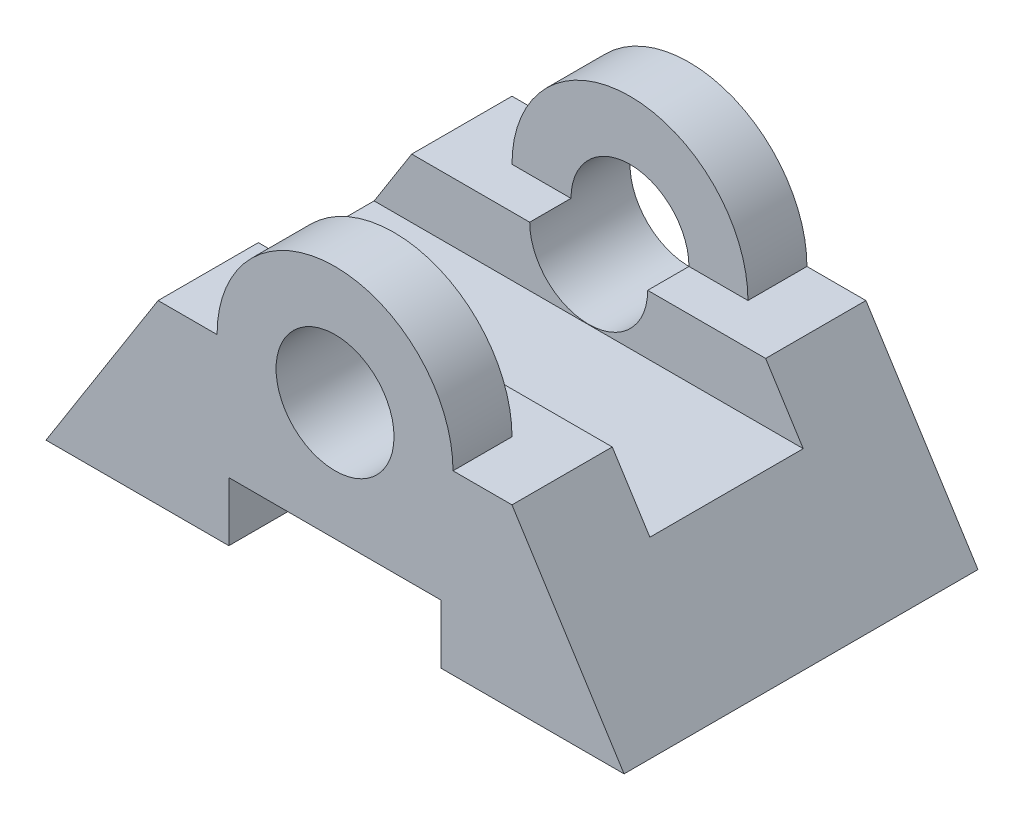
SolidWorks part; units mm, degrees
ref_plane "Front Plane" through (0, 0, 0) normal (0, 0, 1) x (1, 0, 0)
ref_plane "Top Plane" through (0, 0, 0) normal (0, 1, 0) x (1, 0, 0)
ref_plane "Right Plane" through (0, 0, 0) normal (1, 0, 0) x (0, 0, -1)
sketch "Sketch1" plane through (0, 0, 0) normal (0, 0, 1) x (1, 0, 0)
  line L0 (-49, 0) -> (-30, 30)
  line L1 (-30, 30) -> (-20, 30)
  line L2 (-49, 0) -> (-18, 0)
  line L3 (-18, 0) -> (-18, 10)
  line L4 (-18, 10) -> (18, 10)
  line L5 (18, 10) -> (18, 0)
  line L6 (0, 43.941) -> (0, -26.5577) construction
  line L7 (18, 0) -> (18, 10)
  line L8 (49, 0) -> (18, 0)
  line L9 (49, 0) -> (30, 30)
  line L10 (30, 30) -> (20, 30)
  line L11 (-20, 30) -> (20, 30)
  point P2 (0, 10)
  dimension "D1" = 36
  dimension "D2" = 98
  dimension "D3" = 10
  dimension "D4" = 10
  dimension "D5" = 30
extrude "Boss-Extrude1" add sketch "Sketch1" against normal blind 60 contours L6 L11 L1 L0 L2 L3 L4 | L11 L6 L4 L5 L8 L9 L10
ref_plane "Plane1" through (30, 0, 0) normal (1, 0, 0) x (0, 0, -1)
sketch "Sketch3" plane through (30, 0, 0) normal (1, 0, 0) x (0, 0, -1)
  line L0 (17, 30) -> (17, 19.937)
  line L1 (60, 30) -> (0, 30) construction
  line L2 (17, 19.937) -> (43, 19.937)
  line L3 (43, 19.937) -> (43, 30)
  point P4 (0, 0)
  dimension "D1" = 17
  dimension "D2" = 26
extrude "Cut-Extrude1" cut sketch "Sketch3" against normal through all and the other way through all
sketch "Sketch4" plane through (0, 0, 0) normal (0, 0, 1) x (1, 0, 0)
  line L0 (-30, 30) -> (30, 30) construction
  line L1 (-20, 30) -> (20, 30)
  arc A0 (20, 30) -> (-20, 30) centre (0, 30) ccw
  dimension "D1" = 40
extrude "Boss-Extrude2" add sketch "Sketch4" against normal blind 10
sketch "Sketch5" plane through (0, 0, 0) normal (0, 0, 1) x (1, 0, 0)
  circle A0 centre (0, 30) radius 10
  dimension "D1" = 20
extrude "Cut-Extrude2" cut sketch "Sketch5" against normal through all
ref_plane "Plane2" through (0, 0, -30) normal (0, 0, 1) x (1, 0, 0)
mirror "Mirror1" about plane through (0, 0, -30) normal (0, 0, 1) of "Boss-Extrude2"
mirror "Mirror2" about plane through (0, 0, -30) normal (0, 0, 1) of "Cut-Extrude2"
